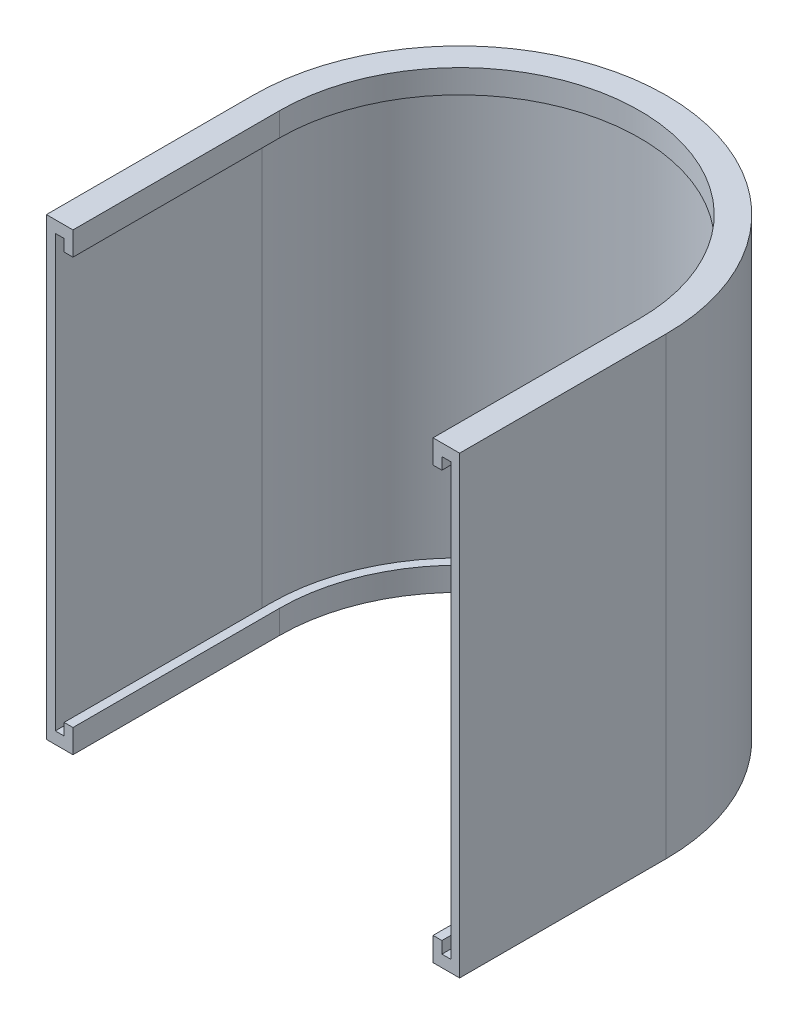
SolidWorks part; units mm, degrees
ref_plane "前视基准面" through (0, 0, 0) normal (0, 0, 1) x (1, 0, 0)
ref_plane "上视基准面" through (0, 0, 0) normal (0, 1, 0) x (1, 0, 0)
ref_plane "右视基准面" through (0, 0, 0) normal (1, 0, 0) x (0, 0, -1)
other "Configuration Table"
sketch "草图1" plane through (0, 0, 0) normal (0, 1, 0) x (1, 0, 0)
  line L2 (-35, 0) -> (-35, -35)
  line L3 (-35, -35) -> (35, -35)
  line L4 (35, 0) -> (35, -35)
  arc A1 (35, 0) -> (-35, 0) centre (0, 0) ccw
extrude "凸台-拉伸1" add sketch "草图1" along normal blind 2
sketch "草图5" plane through (0, 2, 0) normal (0, 1, 0) x (1, 0, 0)
  line L3 (33.5, -35) -> (35, -35)
  line L5 (-33.5, 0) -> (-33.5, -35)
  line L6 (-35, 0) -> (-35, -35)
  line L7 (-35, -35) -> (35, -35)
  line L8 (35, -35) -> (35, 0)
  line L9 (-35, 0) -> (-35, -35)
  line L10 (-35, -35) -> (-33.5, -35)
  line L11 (35, -35) -> (35, 0)
  line L13 (33.5, 0) -> (33.5, -35)
  arc A1 (33.5, 0) -> (-33.5, 0) centre (0, 0) ccw
  arc A2 (35, 0) -> (-35, 0) centre (0, 0) ccw
  arc A3 (35, 0) -> (-35, 0) centre (0, 0) ccw
  dimension "D1" = 0
extrude "凸台-拉伸2" add sketch "草图5" along normal blind 73
sketch "草图6" plane through (0, 2, 0) normal (0, 1, 0) x (1, 0, 0)
  line L0 (-33.5, -35) -> (33.5, -35) construction
  line L2 (-32, 0) -> (-32, -35)
  line L3 (-32, -35) -> (-30.5, -35)
  line L4 (32, 0) -> (32, -35)
  line L5 (30.5, -35) -> (32, -35)
  line L7 (-30.5, 0) -> (-30.5, -35)
  line L9 (30.5, 0) -> (30.5, -35)
  arc A0 (32, 0) -> (-32, 0) centre (0, 0) ccw
  arc A1 (30.5, 0) -> (-30.5, 0) centre (0, 0) ccw
extrude "凸台-拉伸3" add sketch "草图6" along normal blind 2
sketch "草图8" plane through (0, 75, 0) normal (0, 1, 0) x (1, 0, 0)
  line L8 (-35, 0) -> (-35, -35)
  line L9 (-35, -35) -> (35, -35)
  line L10 (35, 0) -> (35, -35)
  arc A2 (35, 0) -> (-35, 0) centre (0, 0) ccw
extrude "凸台-拉伸4" add sketch "草图8" along normal blind 2
sketch "草图10" plane through (0, 75, 0) normal (0, -1, 0) x (1, 0, 0)
  line L0 (-35, 35) -> (35, 35) construction
  line L2 (-32, 0) -> (-32, 35)
  line L3 (-32, 35) -> (-30.5, 35)
  line L4 (32, 0) -> (32, 35)
  line L5 (30.5, 35) -> (32, 35)
  line L7 (-30.5, 0) -> (-30.5, 35)
  line L9 (30.5, 0) -> (30.5, 35)
  arc A0 (-32, 0) -> (32, 0) centre (0, 0) ccw
  arc A1 (-30.5, 0) -> (30.5, 0) centre (0, 0) ccw
extrude "凸台-拉伸5" add sketch "草图10" along normal blind 2
sketch "草图12" plane through (0, 77, 0) normal (0, 1, 0) x (1, 0, 0)
  line L3 (-35, -35) -> (35, -35) construction
  line L5 (-30.5, -30.5) -> (-30.5, -35)
  line L6 (-30.5, 0) -> (-30.5, -30.5)
  line L7 (-30.5, -30.5) -> (30.5, -30.5)
  line L8 (30.5, -30.5) -> (30.5, 0)
  line L9 (-30.5, 0) -> (-30.5, -30.5)
  line L11 (30.5, -30.5) -> (30.5, 0)
  line L12 (-30.5, -35) -> (30.5, -35)
  line L13 (30.5, -30.5) -> (30.5, -35)
  arc A2 (30.5, 0) -> (-30.5, 0) centre (0, 0) ccw
  arc A3 (30.5, 0) -> (-30.5, 0) centre (0, 0) ccw
  dimension "D1" = 4.5
extrude "切除-拉伸1" cut sketch "草图12" against normal blind 80
